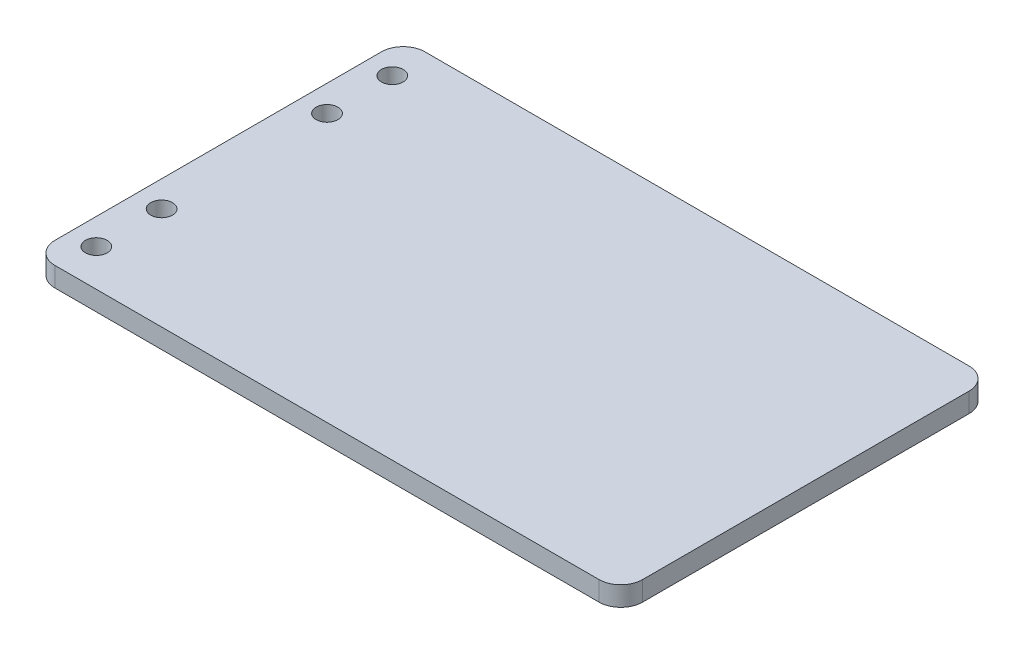
SolidWorks part; units mm, degrees
ref_plane "Plano frontal" through (0, 0, 0) normal (0, 0, 1) x (1, 0, 0)
ref_plane "Plano superior" through (0, 0, 0) normal (0, 1, 0) x (1, 0, 0)
ref_plane "Plano direito" through (0, 0, 0) normal (1, 0, 0) x (0, 0, -1)
sketch "Esboço1" plane through (0, 0, 0) normal (0, 1, 0) x (1, 0, 0)
  line L1 (12.5, -8.5) -> (-12.5, -8.5)
  line L2 (13.5, -7.5) -> (13.5, 7.5)
  line L3 (12.5, 8.5) -> (-12.5, 8.5)
  line L4 (-13.5, -7.5) -> (-13.5, 7.5)
  line L5 (13.5, -8.5) -> (-13.5, 8.5) construction
  line L6 (13.5, 8.5) -> (-13.5, -8.5) construction
  arc A0 (13.5, -7.5) -> (12.5, -8.5) centre (12.5, -7.5) cw
  arc A1 (13.5, 7.5) -> (12.5, 8.5) centre (12.5, 7.5) ccw
  arc A2 (-12.5, 8.5) -> (-13.5, 7.5) centre (-12.5, 7.5) ccw
  arc A3 (-12.5, -8.5) -> (-13.5, -7.5) centre (-12.5, -7.5) cw
  point P0 (0, 0)
  dimension "D3" = 1
  dimension "D1" = 27
  dimension "D2" = 17
extrude "Ressalto-extrusão1" add sketch "Esboço1" along normal mid plane 0.9
sketch "Esboço2" plane through (0, 0.45, 0) normal (0, 1, 0) x (1, 0, 0)
  line L0 (0, 0) -> (-13.5, 0) construction
  line L1 (-13.5, 7.5) -> (-13.5, -7.5) construction
  circle A0 centre (-12.3, 3.8) radius 0.5
  circle A1 centre (-12.3, 6.8) radius 0.5
  circle A2 centre (-12.3, -6.8) radius 0.5
  circle A3 centre (-12.3, -3.8) radius 0.5
  dimension "D1" = 1
  dimension "D2" = 1.2
  dimension "D3" = 6.8
  dimension "D4" = 3
extrude "Corte-extrusão1" cut sketch "Esboço2" against normal through all
